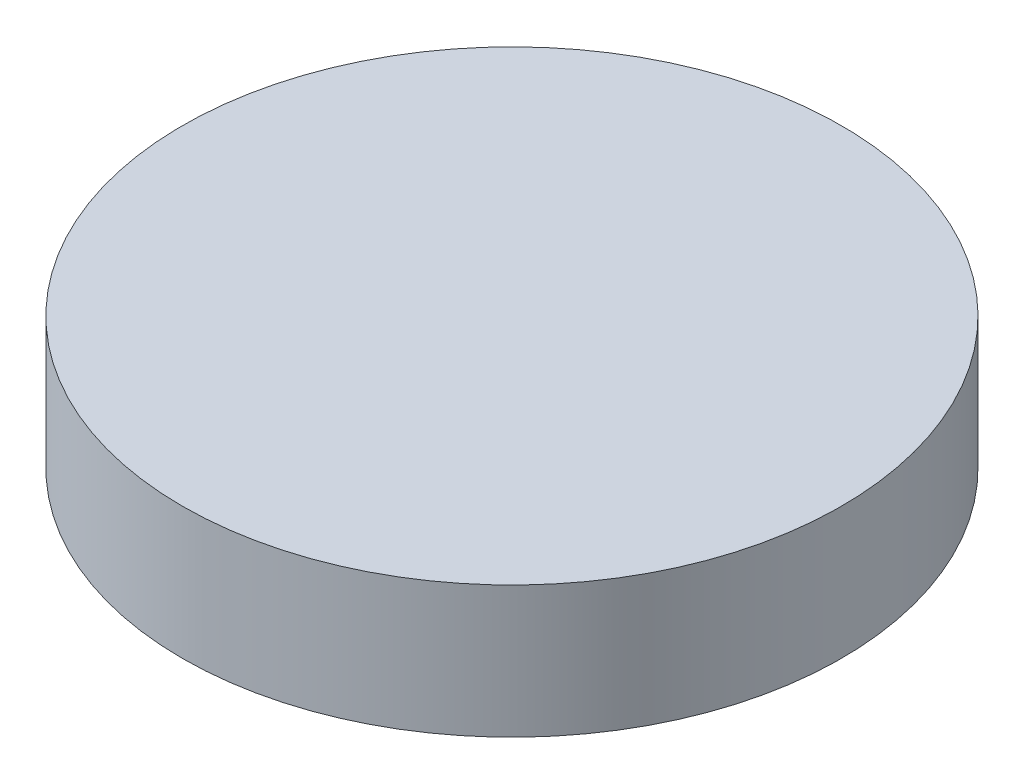
SolidWorks part; units mm, degrees
material "Rubber"
ref_plane "Front Plane" through (0, 0, 0) normal (0, 0, 1) x (1, 0, 0)
ref_plane "Top Plane" through (0, 0, 0) normal (0, 1, 0) x (1, 0, 0)
ref_plane "Right Plane" through (0, 0, 0) normal (1, 0, 0) x (0, 0, -1)
sketch "Sketch2" plane through (0, 0, 0) normal (0, 1, 0) x (1, 0, 0)
  circle A0 centre (0, 0) radius 10
  dimension "D1" = 20
extrude "Boss-Extrude1" add sketch "Sketch2" along normal blind 4
sketch "Sketch3" plane through (0, 4, 0) normal (0, 1, 0) x (1, 0, 0)
  point P0 (0, 0)
equation "\"____ GENERATED PART EXPORTS ____\" = 0"
equation "\"SYS_VersionTag\" = 2"
equation "\"GB_BaseOD\" = 220mm"
equation "\"GB_BasePlateThk\" = 10mm"
equation "\"GB_BenchMountBCD\" = 170mm"
equation "\"GB_BenchHoleClearDia\" = 5.5mm"
equation "\"GB_BenchMountCount\" = 4"
equation "\"GB_FeetEnabled\" = 1"
equation "\"GB_FeetCount\" = 4"
equation "\"GB_FeetOD\" = 20mm"
equation "\"GB_FeetThk\" = 4mm"
equation "\"GB_FeetBCD\" = 180mm"
equation "\"GB_RemovableBallastEnabled\" = 1"
equation "\"GB_RemovableBallastMountBCD\" = 140mm"
equation "\"GB_RemovableBallastMountClearDia\" = 5.5mm"
equation "\"GB_RemovableBallastMountCount\" = 4"
equation "\"D1@Sketch2\"=\"GB_FeetOD\""
equation "\"D1@Boss-Extrude1\"=\"GB_FeetThk\""
